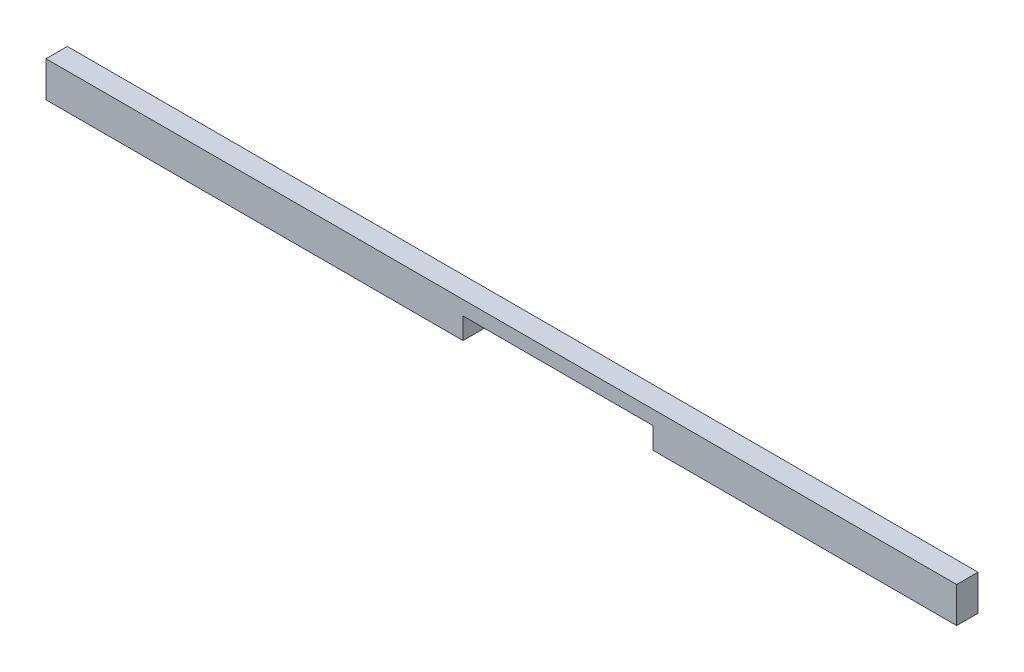
SolidWorks part; units mm, degrees
material "Pine"
ref_plane "Front Plane" through (0, 0, 0) normal (0, 0, 1) x (1, 0, 0)
ref_plane "Top Plane" through (0, 0, 0) normal (0, 1, 0) x (1, 0, 0)
ref_plane "Right Plane" through (0, 0, 0) normal (1, 0, 0) x (0, 0, -1)
sketch "Sketch1" plane through (0, 0, 0) normal (0, 1, 0) x (1, 0, 0)
  line L1 (-406.4, -9.525) -> (406.4, -9.525)
  line L2 (-406.4, -9.525) -> (-406.4, 9.525)
  line L3 (-406.4, 9.525) -> (406.4, 9.525)
  line L4 (406.4, -9.525) -> (406.4, 9.525)
  line L5 (-406.4, -9.525) -> (406.4, 9.525) construction
  line L6 (-406.4, 9.525) -> (406.4, -9.525) construction
  point P0 (0, 0)
  dimension "D1" = 19.05
  dimension "D2" = 812.8
extrude "Boss-Extrude1" add sketch "Sketch1" along normal blind 31.75
sketch "Sketch2" plane through (0, 0, -9.525) normal (0, 0, -1) x (-1, 0, 0)
  line L5 (-135.2061, 0) -> (34.1825, 0)
  line L6 (-135.2061, 19.05) -> (-135.2061, 0)
  line L7 (34.1825, 19.05) -> (-135.2061, 19.05)
  line L12 (34.1825, 0) -> (34.1825, 19.05)
  line L21 (-135.2061, 0) -> (34.1825, 0)
  line L22 (-135.2061, 19.05) -> (-135.2061, 0)
  line L23 (34.1825, 19.05) -> (-135.2061, 19.05)
  line L24 (34.1825, 0) -> (34.1825, 19.05)
  dimension "D1" = 0
extrude "Cut-Extrude1" cut sketch "Sketch2" against normal through all
